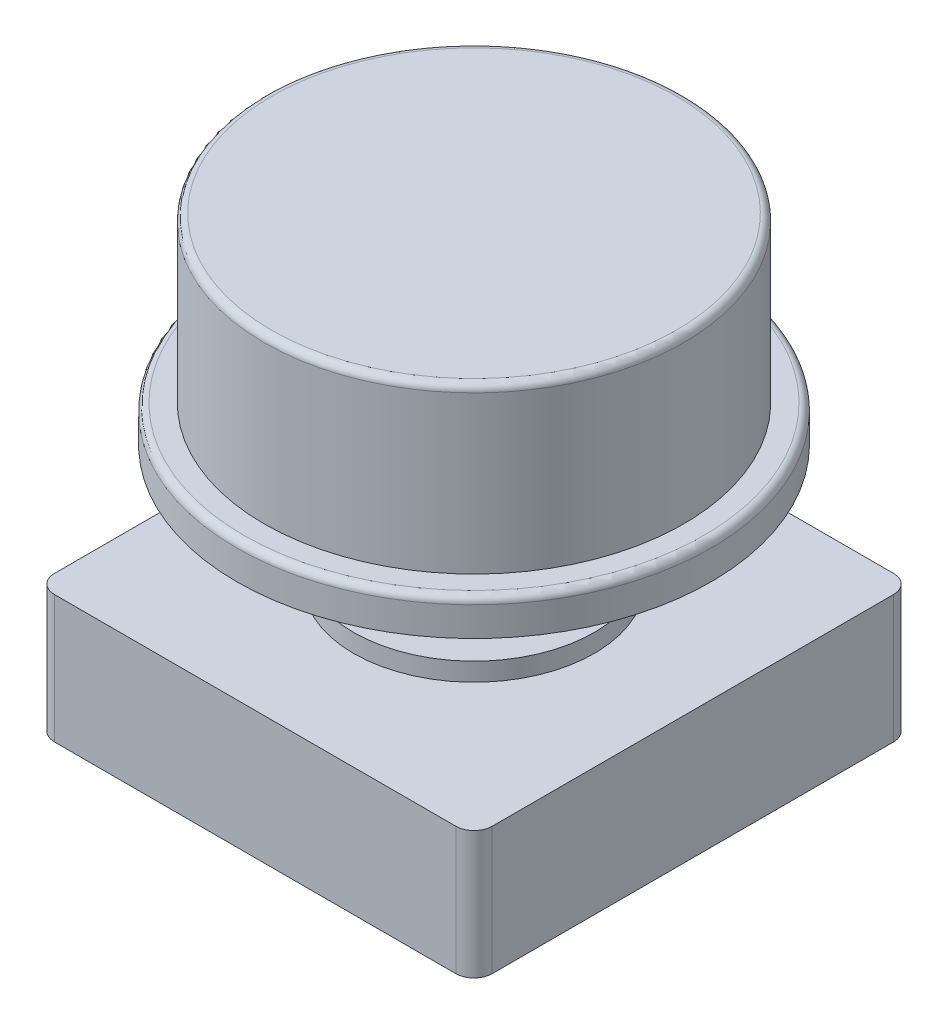
SolidWorks part; units mm, degrees
ref_plane "Plan de face" through (0, 0, 0) normal (0, 0, 1) x (1, 0, 0)
ref_plane "Plan de dessus" through (0, 0, 0) normal (0, 1, 0) x (1, 0, 0)
ref_plane "Plan de droite" through (0, 0, 0) normal (1, 0, 0) x (0, 0, -1)
sketch "Sketch1" plane through (0, 0, 0) normal (0, 1, 0) x (1, 0, 0)
  line L1 (-0.5, 0) -> (-11.5, 0)
  line L2 (0, 0.5) -> (0, 11.5)
  line L3 (-0.5, 12) -> (-11.5, 12)
  line L4 (-12, 0.5) -> (-12, 11.5)
  arc A0 (-11.5, 0) -> (-12, 0.5) centre (-11.5, 0.5) cw
  arc A1 (-0.5, 0) -> (0, 0.5) centre (-0.5, 0.5) ccw
  arc A2 (-0.5, 12) -> (0, 11.5) centre (-0.5, 11.5) cw
  arc A3 (-11.5, 12) -> (-12, 11.5) centre (-11.5, 11.5) ccw
  point P9 (0, 0)
  point P12 (0, 12)
  point P15 (-12, 12)
  dimension "D3" = 0.5
  dimension "D1" = 12
  dimension "D2" = 12
extrude "Boss-Extrude1" add sketch "Sketch1" along normal blind 3.5 contours L4 A3 L3 A2 L2 A1 L1 A0
sketch "Sketch2" plane through (0, 3.5, 0) normal (0, 1, 0) x (1, 0, 0)
  line L0 (-11.8536, 11.8536) -> (-0.1464, 0.1464) construction
  arc A0 (-11.5, 12) -> (-12, 11.5) centre (-11.5, 11.5) ccw construction
  arc A1 (-0.5, 0) -> (0, 0.5) centre (-0.5, 0.5) ccw construction
  circle A2 centre (-6, 6) radius 3.3
  dimension "D1" = 6.6
extrude "Boss-Extrude2" add sketch "Sketch2" along normal blind 0.5
sketch "Sketch3" plane through (0, 4, 0) normal (0, 1, 0) x (1, 0, 0)
  line L0 (-6, 9.3) -> (-6, 2.7) construction
  line L5 (-9.3, 6) -> (-2.7, 6) construction
  line L7 (-7.5, 7.5) -> (-4.5, 7.5)
  line L8 (-7.5, 7.5) -> (-7.5, 4.5)
  line L9 (-7.5, 4.5) -> (-4.5, 4.5)
  line L10 (-4.5, 7.5) -> (-4.5, 4.5)
  circle A0 centre (-6, 6) radius 3.3 construction
  circle A1 centre (-6, 6) radius 3.3 construction
  dimension "D1" = 1.5
  dimension "D2" = 1.5
  dimension "D3" = 1.5
  dimension "D4" = 1.5
extrude "Boss-Extrude3" add sketch "Sketch3" along normal blind 2.8
sketch "Sketch4" plane through (0, 6.8, 0) normal (0, 1, 0) x (1, 0, 0)
  line L0 (-6, 7.5) -> (-6, 4.5) construction
  line L1 (-4.5, 7.5) -> (-7.5, 7.5) construction
  line L2 (-7.5, 4.5) -> (-4.5, 4.5) construction
  circle A0 centre (-6, 6) radius 6.5
  dimension "D1" = 13
extrude "Boss-Extrude4" add sketch "Sketch4" along normal blind 1
sketch "Sketch5" plane through (0, 7.8, 0) normal (0, 1, 0) x (1, 0, 0)
  circle A0 centre (-6, 6) radius 5.75
  dimension "D1" = 11.5
extrude "Boss-Extrude5" add sketch "Sketch5" along normal blind 4.5
fillet "Fillet1" radius 0.2 2 edges at (-6, 7.8, 0.5) (-6, 12.3, -0.25)
